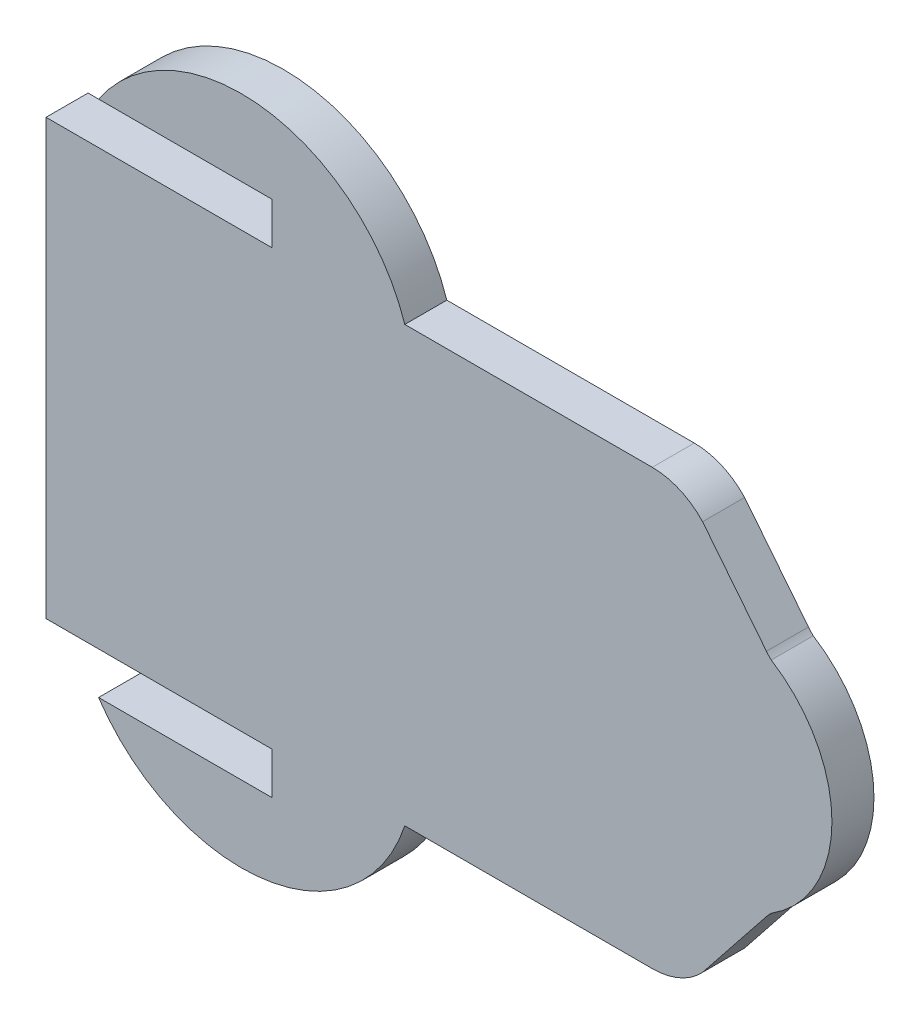
SolidWorks part; units mm, degrees
ref_plane "Front" through (0, 0, 0) normal (0, 0, 1) x (1, 0, 0)
ref_plane "Top" through (0, 0, 0) normal (0, 1, 0) x (1, 0, 0)
ref_plane "Right" through (0, 0, 0) normal (1, 0, 0) x (0, 0, -1)
sketch "Sketch1" plane through (0, 0, 0) normal (0, 0, 1) x (1, 0, 0)
  line L0 (534.5071, 1.5666) -> (534.5071, -29.4334)
  line L1 (581.3835, -27.8663) -> (585.9435, -22.1357)
  line L2 (538.2586, -32.4334) -> (550.6431, -32.4334)
  line L3 (534.5071, -29.4334) -> (550.6431, -29.4334)
  line L4 (534.5071, -13.9334) -> (590.6215, -13.9334) construction
  line L5 (560.1222, -29.4334) -> (577.4542, -29.4334)
  line L6 (550.6431, -32.4334) -> (550.6431, -29.4334)
  line L7 (577.4542, -29.4334) -> (577.7934, -29.4334)
  line L8 (577.4542, 1.5666) -> (577.7934, 1.5666)
  line L9 (550.6431, 4.5666) -> (550.6431, 1.5666)
  line L10 (560.1222, 1.5666) -> (577.4542, 1.5666)
  line L11 (534.5071, 1.5666) -> (550.6431, 1.5666)
  line L12 (538.2586, 4.5666) -> (550.6431, 4.5666)
  line L13 (581.3835, -0.0005) -> (585.9435, -5.7311)
  arc A0 (586.2883, -21.7618) -> (586.2883, -6.1051) centre (581.3835, -13.9334) ccw
  arc A1 (586.2883, -6.1051) -> (585.9435, -5.7311) centre (588.68, -3.5537) cw
  arc A2 (577.7934, 1.5666) -> (581.3835, -0.0005) centre (577.7934, -3.3293) cw
  arc A3 (538.2586, -32.4334) -> (560.1222, -29.4334) centre (548.4576, -25.5931) ccw
  arc A4 (577.7934, -29.4334) -> (581.3835, -27.8663) centre (577.7934, -24.5375) ccw
  arc A5 (586.2883, -21.7618) -> (585.9435, -22.1357) centre (588.68, -24.3131) ccw
  arc A6 (538.2586, 4.5666) -> (560.1222, 1.5666) centre (548.4576, -2.2737) cw
  dimension "D1" = 18.5
  dimension "D2" = 3
extrude "Base-Extrude" add sketch "Sketch1" along normal blind 3
